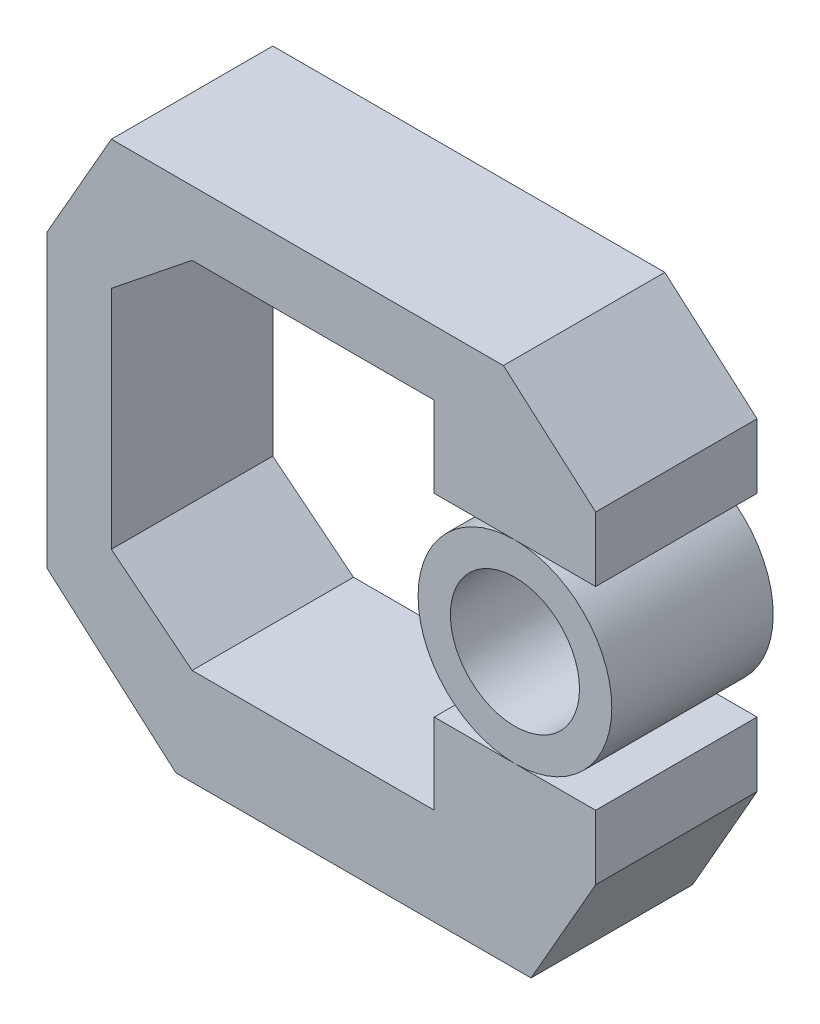
SolidWorks part; units mm, degrees
ref_plane "Front Plane" through (0, 0, 0) normal (0, 0, 1) x (1, 0, 0)
ref_plane "Top Plane" through (0, 0, 0) normal (0, 1, 0) x (1, 0, 0)
ref_plane "Right Plane" through (0, 0, 0) normal (1, 0, 0) x (0, 0, -1)
sketch "Sketch1" plane through (0, 0, 0) normal (0, 0, 1) x (1, 0, 0)
  line L0 (-5, -6) -> (5, -6)
  line L1 (5, -6) -> (5, -10)
  line L2 (5, -10) -> (1, -17)
  line L3 (1, -17) -> (-21, -17)
  line L4 (-21, -17) -> (-29, -10)
  line L5 (-29, -10) -> (-29, 8)
  line L6 (-29, 8) -> (-25, 15)
  line L7 (-25, 15) -> (-0.7143, 15)
  line L8 (-5, -6) -> (-5, -11)
  line L9 (-5, -11) -> (-20, -11)
  line L10 (-20, -11) -> (-25, -7)
  line L11 (-25, -7) -> (-25, 7)
  line L12 (-25, 7) -> (-20, 11)
  line L13 (-0.7143, 15) -> (5, 10)
  line L14 (5, 10) -> (5, 6)
  line L15 (5, 6) -> (-5, 6)
  line L16 (-5, 6) -> (-5, 11)
  line L17 (-5, 11) -> (-20, 11)
  circle A0 centre (0, 0) radius 4
  circle A1 centre (0, 0) radius 6
  point P6 (0, -6)
  dimension "D1" = 8
  dimension "D2" = 12
  dimension "D3" = 22
  dimension "D4" = 4
  dimension "D5" = 4
  dimension "D6" = 7
  dimension "D7" = 8
  dimension "D8" = 7
  dimension "D9" = 18
  dimension "D10" = 10
  dimension "D11" = 5
  dimension "D12" = 15
  dimension "D13" = 4
  dimension "D14" = 5
  dimension "D15" = 14
  dimension "D16" = 32
extrude "Boss-Extrude1" add sketch "Sketch1" along normal mid plane 10 contours L17 L16 L15 L14 L13 L7 L6 L5 L4 L3 L2 L1 L0 L8 L9 L10 L11 L12 | A1 A0
